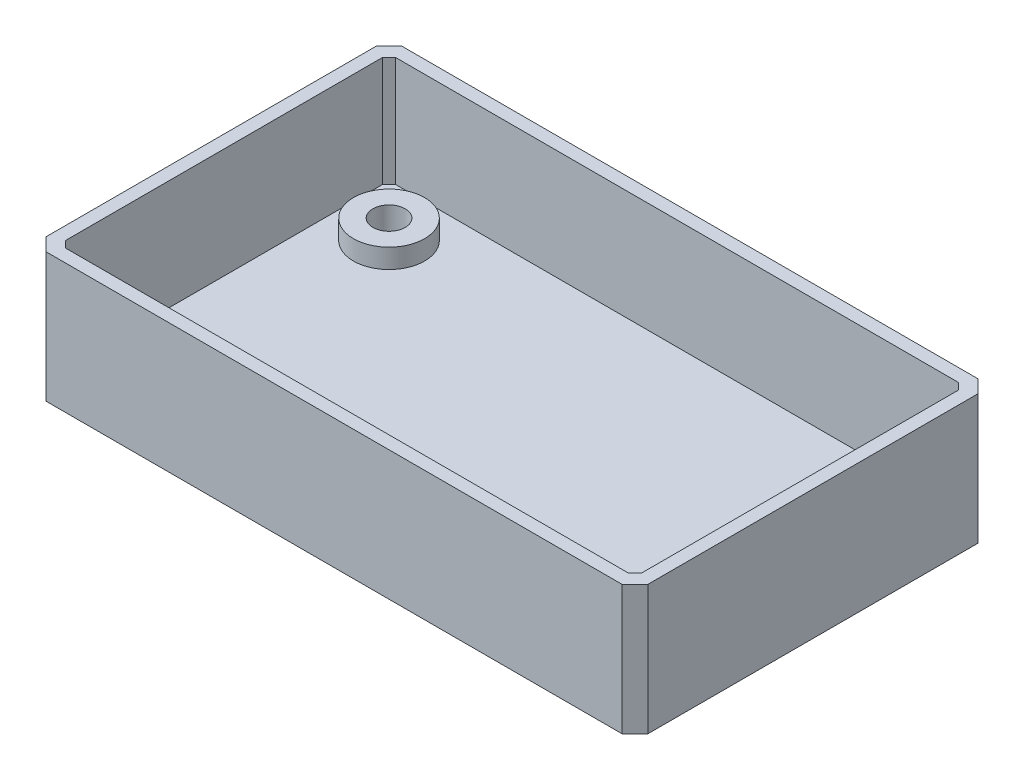
SolidWorks part; units mm, degrees
ref_plane "Front Plane" through (0, 0, 0) normal (0, 0, 1) x (1, 0, 0)
ref_plane "Top Plane" through (0, 0, 0) normal (0, 1, 0) x (1, 0, 0)
ref_plane "Right Plane" through (0, 0, 0) normal (1, 0, 0) x (0, 0, -1)
sketch "Sketch1" plane through (0, 0, 0) normal (0, 1, 0) x (1, 0, 0)
  line L1 (-8, 8) -> (81, 8)
  line L2 (-8, 8) -> (-8, -43)
  line L3 (-8, -43) -> (81, -43)
  line L4 (81, 8) -> (81, -43)
  circle A0 centre (0, 0) radius 2.5
  circle A1 centre (73, 0) radius 2.5
  circle A2 centre (0, -35) radius 2.5
  circle A3 centre (73, -35) radius 2.5
  point P9 (0, 0)
  dimension "D1" = 5
  dimension "D2" = 73
  dimension "D3" = 35
  dimension "D4" = 8
  dimension "D5" = 8
  dimension "D6" = 8
  dimension "D7" = 8
extrude "Boss-Extrude1" add sketch "Sketch1" along normal blind 3
sketch "Sketch2" plane through (0, 3, 0) normal (0, 1, 0) x (1, 0, 0)
  circle A0 centre (0, 0) radius 5.5
  circle A1 centre (73, 0) radius 5.5
  circle A2 centre (73, -35) radius 5.5
  circle A3 centre (0, -35) radius 5.5
  circle A4 centre (0, -35) radius 2.5 construction
  circle A5 centre (73, -35) radius 2.5 construction
  circle A6 centre (73, 0) radius 2.5 construction
  circle A7 centre (0, 0) radius 2.5 construction
  circle A8 centre (0, -35) radius 2.5
  circle A9 centre (73, -35) radius 2.5
  circle A10 centre (73, 0) radius 2.5
  circle A11 centre (0, 0) radius 2.5
  dimension "D1" = 11
extrude "Boss-Extrude2" add sketch "Sketch2" along normal blind 3
sketch "Sketch3" plane through (0, 0, 0) normal (0, -1, 0) x (1, 0, 0)
  line L4 (-8, 43) -> (-8, -8)
  line L5 (-8, -8) -> (81, -8)
  line L6 (81, -8) -> (81, 43)
  line L7 (81, 43) -> (-8, 43)
  line L8 (-8, 43) -> (-8, -8)
  line L9 (-8, -8) -> (81, -8)
  line L10 (81, -8) -> (81, 43)
  line L11 (81, 43) -> (-8, 43)
  line L16 (-10, 45) -> (-10, -10)
  line L17 (-10, -10) -> (83, -10)
  line L18 (83, -10) -> (83, 45)
  line L19 (83, 45) -> (-10, 45)
  line L20 (-10, 45) -> (-10, -10)
  line L21 (-10, -10) -> (83, -10)
  line L22 (83, -10) -> (83, 45)
  line L23 (83, 45) -> (-10, 45)
  dimension "D1" = 0
  dimension "D2" = 2
extrude "Boss-Extrude3" add sketch "Sketch3" against normal blind 20
chamfer "Chamfer1" distance 2 angle 45 4 edges at (-10, 10, -10) (83, 10, -10) (83, 10, 45) (-10, 10, 45)
chamfer "Chamfer2" distance 1 angle 45 4 edges at (-8, 11.5, 43) (-8, 11.5, -8) (81, 11.5, -8) (81, 11.5, 43)
sketch "Sketch4" plane through (0, 6, 0) normal (0, 1, 0) x (1, 0, 0)
  line L1 (80.0775, -42.5667) -> (-6.9225, -42.5667)
  line L2 (80.0775, -42.5667) -> (80.0775, 7.4333)
  line L3 (80.0775, 7.4333) -> (-6.9225, 7.4333)
  line L4 (-6.9225, -42.5667) -> (-6.9225, 7.4333)
  dimension "D1" = 87
  dimension "D2" = 50
equation "\"D4@Sketch1\"=\"D5@Sketch1\""
equation "\"D7@Sketch1\"=\"D5@Sketch1\""
equation "\"D6@Sketch1\"=\"D5@Sketch1\""
